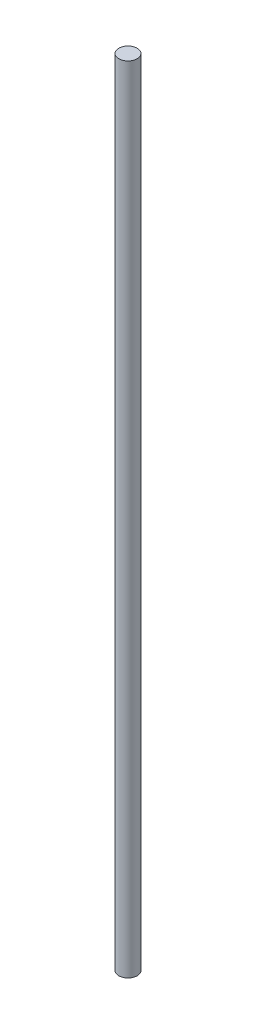
SolidWorks part; units mm, degrees
material "AISI Type 316L stainless steel"
ref_plane "Front Plane" through (0, 0, 0) normal (0, 0, 1) x (1, 0, 0)
ref_plane "Top Plane" through (0, 0, 0) normal (0, 1, 0) x (1, 0, 0)
ref_plane "Right Plane" through (0, 0, 0) normal (1, 0, 0) x (0, 0, -1)
sketch "Sketch1" plane through (0, 0, 0) normal (0, 1, 0) x (1, 0, 0)
  circle A0 centre (0, 0) radius 3
  dimension "D1" = 6
extrude "Boss-Extrude1" add sketch "Sketch1" along normal blind 260
